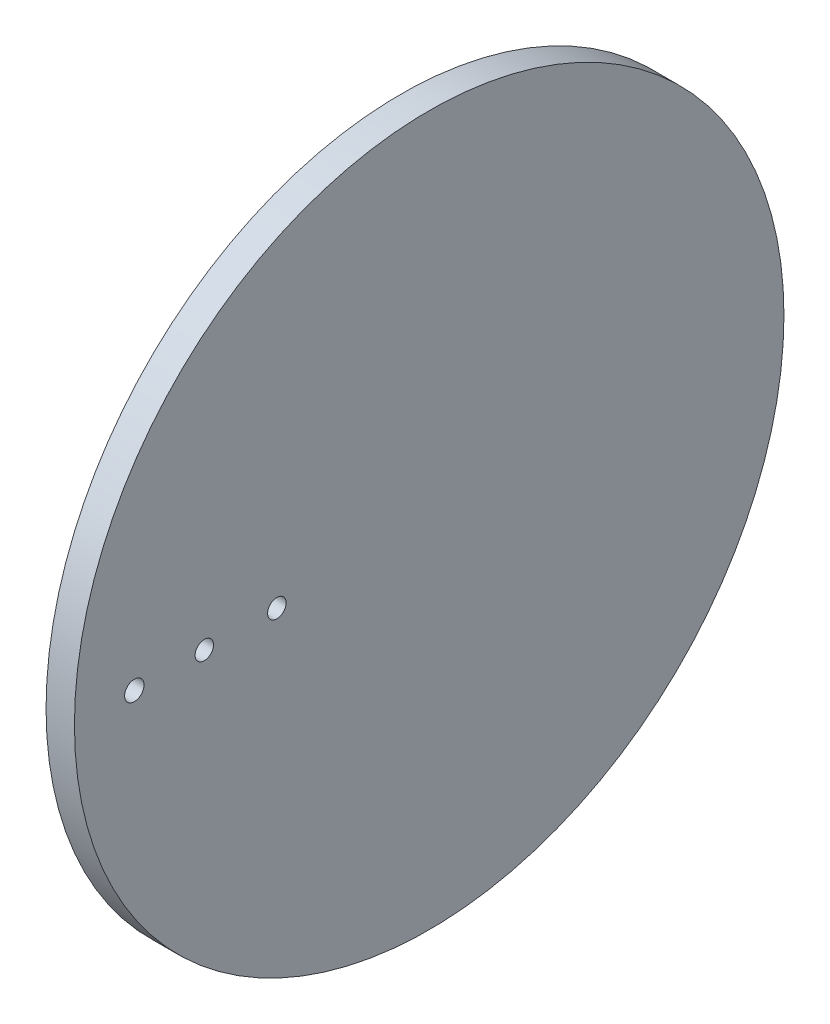
SolidWorks part; units mm, degrees
ref_plane "Alzado" through (0, 0, 0) normal (0, 0, 1) x (1, 0, 0)
ref_plane "Planta" through (0, 0, 0) normal (0, 1, 0) x (1, 0, 0)
ref_plane "Vista lateral" through (0, 0, 0) normal (1, 0, 0) x (0, 0, -1)
sketch "Croquis1" plane through (0, 0, 0) normal (1, 0, 0) x (0, 0, -1)
  circle A0 centre (0, 0) radius 37.5
  dimension "D1" = 75
extrude "Saliente-Extruir1" add sketch "Croquis1" along normal blind 3
sketch "Croquis2" plane through (0, 0, 0) normal (-1, 0, 0) x (0, 0, 1)
  circle A0 centre (0, 0) radius 32.4822
  circle A1 centre (0, 0) radius 29.9595
  circle A2 centre (0, 0) radius 24.9973
  circle A3 centre (0, 0) radius 22.4956
  circle A4 centre (0, 0) radius 17.468
  circle A5 centre (0, 0) radius 14.9582
extrude "Cortar-Extruir1" cut sketch "Croquis2" against normal blind 1 contours A0 A1 | A2 A3 | A4 A5
sketch "Croquis3" plane through (0, 0, 0) normal (-1, 0, 0) x (0, 0, 1)
  line L0 (0, 0) -> (37.5, 0) construction
  circle A0 centre (0, 0) radius 37.5 construction
  circle A1 centre (16.1017, 0) radius 0.9767
  circle A2 centre (23.769, 0) radius 0.9733
  circle A3 centre (31.1682, 0) radius 1.0269
extrude "Cortar-Extruir2" cut sketch "Croquis3" against normal blind 3 contours A1 | A2 | A3
sketch "Croquis4" plane through (0, 0, 0) normal (-1, 0, 0) x (0, 0, 1)
  line L0 (0, 0) -> (37.5, 0) construction
  circle A0 centre (0, 0) radius 37.5 construction
  circle A1 centre (16.1017, 0) radius 0.9767 construction
  circle A2 centre (23.769, 0) radius 0.9733 construction
  circle A3 centre (31.1682, 0) radius 1.0269 construction
  dimension "D1" = 16.1017
  dimension "D2" = 23.769
  dimension "D3" = 31.1682
